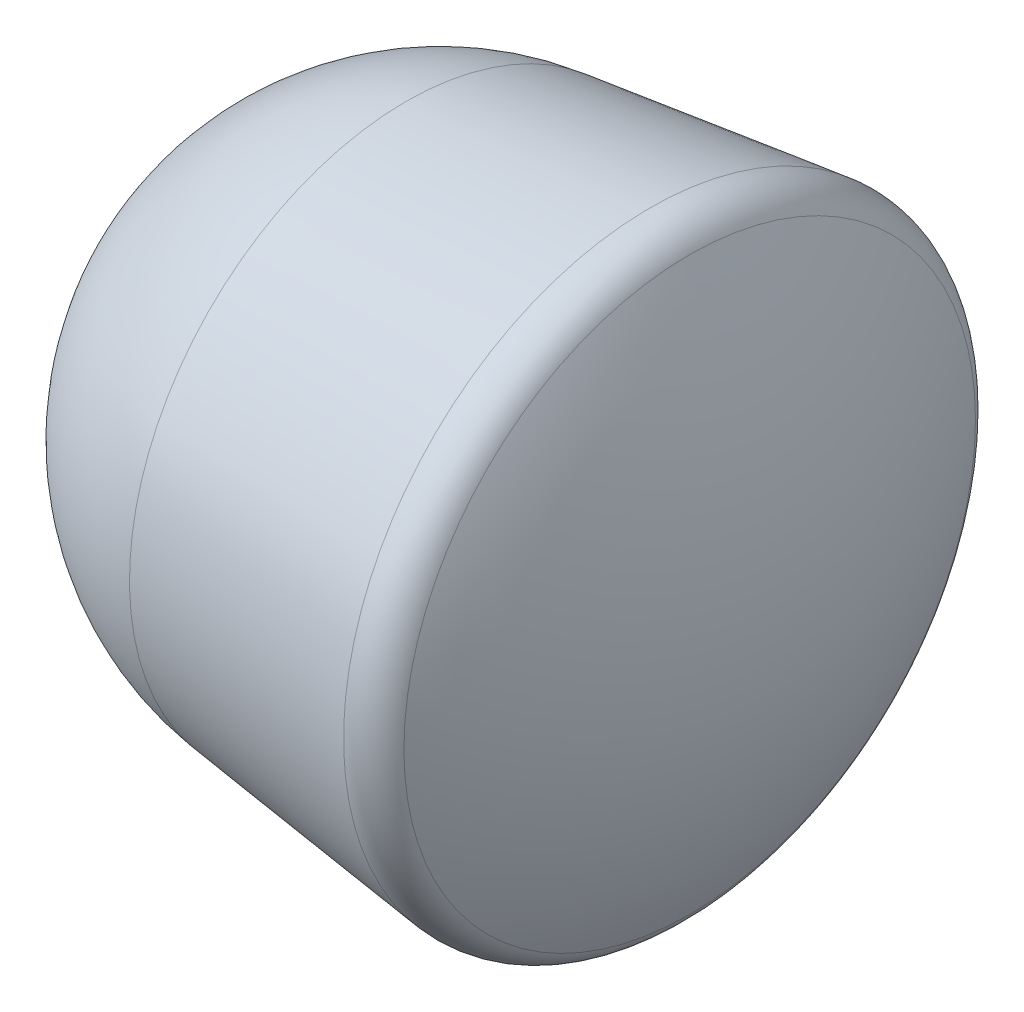
SolidWorks part; units mm, degrees
ref_plane "Piano frontale" through (0, 0, 0) normal (0, 0, 1) x (1, 0, 0)
ref_plane "Piano superiore" through (0, 0, 0) normal (0, 1, 0) x (1, 0, 0)
ref_plane "Piano destro" through (0, 0, 0) normal (1, 0, 0) x (0, 0, -1)
sketch "Schizzo1" plane through (0, 0, 0) normal (0, 0, 1) x (1, 0, 0)
  line L0 (877.245, 991.5451) -> (1752.0406, 1098.9565)
  line L1 (2142, 0) -> (0, 0)
  line L2 (1769.1023, 1100) -> (1769.1023, 0) construction
  arc A0 (1752.0406, 1098.9565) -> (1893.5387, 1024.1527) centre (1769.1023, 960) cw
  arc A1 (1893.5387, 1024.1527) -> (2142, 0) centre (-93, 0) cw
  arc A2 (0, 0) -> (877.245, 991.5451) centre (998.9914, 0) cw
  point P9 (980.114, -461.7899)
  point P10 (0, 0)
  point P11 (0, 0)
  point P12 (0, 0)
  point P13 (0, 0)
  point P14 (0, 0)
  point P17 (0, 0)
  point P18 (2139.7802, 97.4928)
  dimension "D1" = 2235
  dimension "D2" = 140
  dimension "D3" = 2142
  dimension "D4" = 7
  dimension "D5" = 1100
revolve "Rivoluzione1" add sketch "Schizzo1" angle 360 about L1
